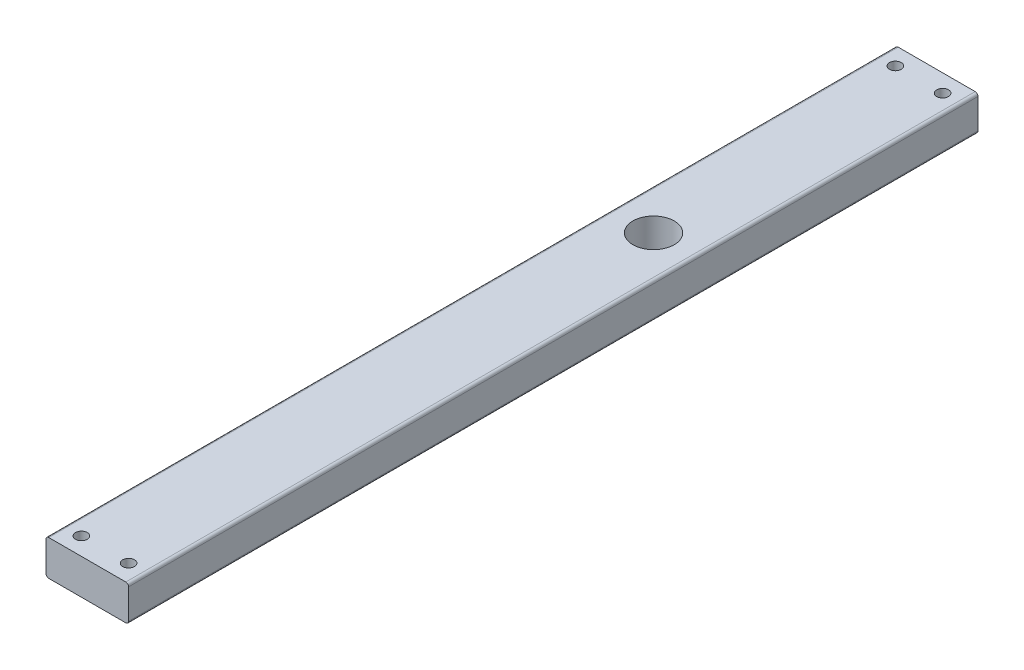
SolidWorks part; units mm, degrees
material "Pine"
ref_plane "Front Plane" through (0, 0, 0) normal (0, 0, 1) x (1, 0, 0)
ref_plane "Top Plane" through (0, 0, 0) normal (0, 1, 0) x (1, 0, 0)
ref_plane "Right Plane" through (0, 0, 0) normal (1, 0, 0) x (0, 0, -1)
sketch "Sketch1" plane through (0, 0, 0) normal (0, 0, 1) x (1, 0, 0)
  line L1 (41.45, -19.05) -> (-41.45, -19.05)
  line L2 (44.45, -16.05) -> (44.45, 16.05)
  line L3 (41.45, 19.05) -> (-41.45, 19.05)
  line L4 (-44.45, -16.05) -> (-44.45, 16.05)
  line L5 (44.45, -19.05) -> (-44.45, 19.05) construction
  line L6 (44.45, 19.05) -> (-44.45, -19.05) construction
  arc A0 (-41.45, -19.05) -> (-44.45, -16.05) centre (-41.45, -16.05) cw
  arc A1 (-41.45, 19.05) -> (-44.45, 16.05) centre (-41.45, 16.05) ccw
  arc A2 (44.45, 16.05) -> (41.45, 19.05) centre (41.45, 16.05) ccw
  arc A3 (41.45, -19.05) -> (44.45, -16.05) centre (41.45, -16.05) ccw
  point P0 (0, 0)
  dimension "D3" = 3
  dimension "D1" = 88.9
  dimension "D2" = 38.1
extrude "Boss-Extrude1" add sketch "Sketch1" along normal blind 914.4
sketch "Sketch2" plane through (0, 19.05, 0) normal (0, 1, 0) x (1, 0, 0)
  line L1 (41.45, 0) -> (-41.45, 0) construction
  circle A0 centre (0, -304.8) radius 22.225
  point P2 (0, -382.4129)
  dimension "D1" = 44.45
  dimension "D2" = 304.8
extrude "Cut-Extrude1" cut sketch "Sketch2" against normal through all
sketch "Sketch3" plane through (0, 19.05, 0) normal (0, 1, 0) x (1, 0, 0)
  line L0 (-25.4, -19.05) -> (25.4, -19.05) construction
  line L1 (25.4, -19.05) -> (25.4, -895.35) construction
  line L2 (25.4, -895.35) -> (-25.4, -895.35) construction
  line L3 (-25.4, -895.35) -> (-25.4, -19.05) construction
  line L5 (41.45, 0) -> (-41.45, 0) construction
  line L6 (44.45, -914.4) -> (44.45, 0) construction
  line L7 (41.45, -914.4) -> (-41.45, -914.4) construction
  point P0 (-25.4, -895.35)
  point P2 (25.4, -895.35)
  point P4 (-25.4, -19.05)
  point P6 (25.4, -19.05)
  point P22 (0, -19.05)
  dimension "D1" = 19.05
  dimension "D2" = 19.05
  dimension "D3" = 19.05
hole_wizard "1/2 (0.5) Diameter Hole1" positions "Sketch3" profile "Sketch4" hole size "1/2" standard "ANSI Inch" end condition through all
sketch "Sketch4" plane through (-25.4, 19.05, 895.35) normal (1, 0, 0) x (0, 0, 1)
  line L0 (0, 0) -> (0, 38.1)
  line L1 (0, 38.1) -> (6.35, 38.1)
  line L2 (6.35, 38.1) -> (6.35, 0)
  line L5 (6.35, 0) -> (0, 0)
  line L11 (0, -6.35) -> (0, 107.95) construction
  dimension "Thru Hole Dia." = 12.7
  dimension "Thru Hole Depth" = 38.1
equation "\"ChainSeperation\"= 80"
